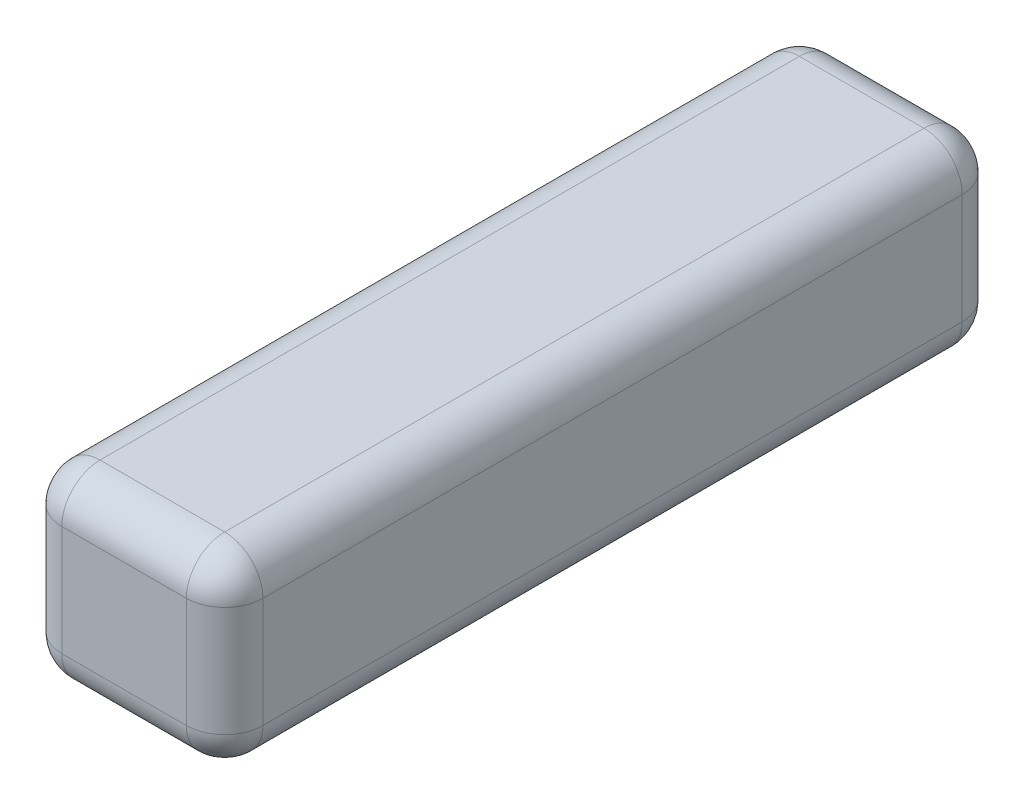
SolidWorks part; units mm, degrees
ref_plane "Front Plane" through (0, 0, 0) normal (0, 0, 1) x (1, 0, 0)
ref_plane "Top Plane" through (0, 0, 0) normal (0, 1, 0) x (1, 0, 0)
ref_plane "Right Plane" through (0, 0, 0) normal (1, 0, 0) x (0, 0, -1)
sketch "Sketch1" plane through (0, 0, 0) normal (0, 0, 1) x (1, 0, 0)
  line L1 (-13.335, -12.3825) -> (13.335, -12.3825)
  line L2 (-13.335, -12.3825) -> (-13.335, 12.3825)
  line L3 (-13.335, 12.3825) -> (13.335, 12.3825)
  line L4 (13.335, -12.3825) -> (13.335, 12.3825)
  dimension "D1" = 26.67
  dimension "D2" = 24.765
  dimension "D3" = 13.335
  dimension "D4" = 12.3825
extrude "Boss-Extrude1" add sketch "Sketch1" along normal blind 102.87
fillet "Fillet1" radius 5.08 12 edges at (13.335, 12.3825, 51.435) (13.335, 0, 0) (0, 12.3825, 0) (13.335, -12.3825, 51.435) (0, -12.3825, 0) (-13.335, 12.3825, 51.435) (-13.335, -12.3825, 51.435) (-13.335, 0, 0) (0, 12.3825, 102.87) (13.335, 0, 102.87) (0, -12.3825, 102.87) (-13.335, 0, 102.87)
sketch "Sketch2" plane through (0, 0, 0) normal (0, 0, -1) x (-1, 0, 0)
  line L0 (8.255, -12.3825) -> (-8.255, -12.3825) construction
  line L1 (-5.715, -0.3175) -> (5.715, -0.3175)
  line L2 (-5.715, -0.3175) -> (-5.715, -4.7625)
  line L3 (-5.715, -4.7625) -> (5.715, -4.7625)
  line L4 (5.715, -0.3175) -> (5.715, -4.7625)
  line L5 (-2.54, 2.2225) -> (2.54, 2.2225)
  line L6 (-3.4925, 4.7625) -> (3.4925, 4.7625)
  line L7 (3.4925, 4.7625) -> (3.4925, 3.4925)
  line L8 (-3.4925, 4.7625) -> (-3.4925, 3.4925)
  line L9 (-3.4925, 3.4925) -> (-2.54, 2.2225)
  line L10 (2.54, 2.2225) -> (3.4925, 3.4925)
  point P4 (0, -4.7625)
  point P10 (0, 2.2225)
  point P11 (0, -0.3175)
  point P14 (0, 4.7625)
  dimension "D1" = 11.43
  dimension "D2" = 4.445
  dimension "D3" = 0
  dimension "D4" = 7.62
  dimension "D5" = 5.08
  dimension "D6" = 2.54
  dimension "D7" = 0
  dimension "D8" = 6.985
  dimension "D9" = 2.54
  dimension "D10" = 0
  dimension "D11" = 1.27
  dimension "D12" = 1.27
extrude "Cut-Extrude1" cut sketch "Sketch2" against normal blind 12.7
